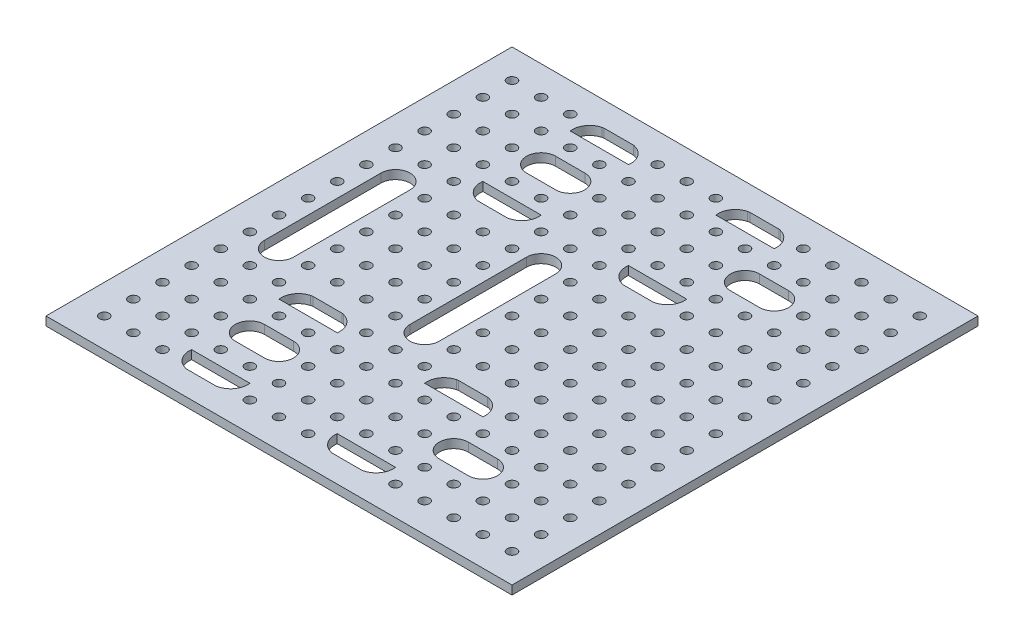
SolidWorks part; units mm, degrees
ref_plane "前视基准面" through (0, 0, 0) normal (0, 0, 1) x (1, 0, 0)
ref_plane "上视基准面" through (0, 0, 0) normal (0, 1, 0) x (1, 0, 0)
ref_plane "右视基准面" through (0, 0, 0) normal (1, 0, 0) x (0, 0, -1)
sketch "草图1" plane through (0, 0, 0) normal (0, 1, 0) x (1, 0, 0)
  line L1 (-80, -80) -> (80, -80)
  line L2 (-80, -80) -> (-80, 80)
  line L3 (-80, 80) -> (80, 80)
  line L4 (80, -80) -> (80, 80)
  line L5 (-80, -80) -> (80, 80) construction
  line L6 (-80, 80) -> (80, -80) construction
  point P0 (0, 0)
  dimension "D1" = 160
  dimension "D2" = 160
extrude "凸台-拉伸1" add sketch "草图1" along normal blind 3 contours L2 L1 L4 L3
sketch "草图3" plane through (0, 3, 0) normal (0, 1, 0) x (1, 0, 0)
  line L0 (-80, 80) -> (80, 80) construction
  line L2 (-80, -80) -> (-80, 80) construction
  circle A0 centre (-70, 70) radius 1.65
  circle A1 centre (-60, 70) radius 1.65
  circle A2 centre (-50, 70) radius 1.65
  circle A3 centre (-40, 70) radius 1.65
  circle A4 centre (-30, 70) radius 1.65
  circle A5 centre (-20, 70) radius 1.65
  circle A6 centre (-10, 70) radius 1.65
  circle A7 centre (0, 70) radius 1.65
  circle A8 centre (10, 70) radius 1.65
  circle A9 centre (20, 70) radius 1.65
  circle A10 centre (30, 70) radius 1.65
  circle A11 centre (40, 70) radius 1.65
  circle A12 centre (50, 70) radius 1.65
  circle A13 centre (60, 70) radius 1.65
  circle A14 centre (70, 70) radius 1.65
  circle A15 centre (-60, 60) radius 1.65
  circle A16 centre (-50, 60) radius 1.65
  circle A17 centre (-40, 60) radius 1.65
  circle A18 centre (-30, 60) radius 1.65
  circle A19 centre (-20, 60) radius 1.65
  circle A20 centre (-10, 60) radius 1.65
  circle A21 centre (0, 60) radius 1.65
  circle A22 centre (10, 60) radius 1.65
  circle A23 centre (20, 60) radius 1.65
  circle A24 centre (30, 60) radius 1.65
  circle A25 centre (40, 60) radius 1.65
  circle A26 centre (50, 60) radius 1.65
  circle A27 centre (60, 60) radius 1.65
  circle A28 centre (70, 60) radius 1.65
  circle A29 centre (-60, 50) radius 1.65
  circle A30 centre (-50, 50) radius 1.65
  circle A31 centre (-40, 50) radius 1.65
  circle A32 centre (-30, 50) radius 1.65
  circle A33 centre (-20, 50) radius 1.65
  circle A34 centre (-10, 50) radius 1.65
  circle A35 centre (0, 50) radius 1.65
  circle A36 centre (10, 50) radius 1.65
  circle A37 centre (20, 50) radius 1.65
  circle A38 centre (30, 50) radius 1.65
  circle A39 centre (40, 50) radius 1.65
  circle A40 centre (50, 50) radius 1.65
  circle A41 centre (60, 50) radius 1.65
  circle A42 centre (70, 50) radius 1.65
  circle A43 centre (-60, 40) radius 1.65
  circle A44 centre (-50, 40) radius 1.65
  circle A45 centre (-40, 40) radius 1.65
  circle A46 centre (-30, 40) radius 1.65
  circle A47 centre (-20, 40) radius 1.65
  circle A48 centre (-10, 40) radius 1.65
  circle A49 centre (0, 40) radius 1.65
  circle A50 centre (10, 40) radius 1.65
  circle A51 centre (20, 40) radius 1.65
  circle A52 centre (30, 40) radius 1.65
  circle A53 centre (40, 40) radius 1.65
  circle A54 centre (50, 40) radius 1.65
  circle A55 centre (60, 40) radius 1.65
  circle A56 centre (70, 40) radius 1.65
  circle A57 centre (-60, 30) radius 1.65
  circle A58 centre (-50, 30) radius 1.65
  circle A59 centre (-40, 30) radius 1.65
  circle A60 centre (-30, 30) radius 1.65
  circle A61 centre (-20, 30) radius 1.65
  circle A62 centre (-10, 30) radius 1.65
  circle A63 centre (0, 30) radius 1.65
  circle A64 centre (10, 30) radius 1.65
  circle A65 centre (20, 30) radius 1.65
  circle A66 centre (30, 30) radius 1.65
  circle A67 centre (40, 30) radius 1.65
  circle A68 centre (50, 30) radius 1.65
  circle A69 centre (60, 30) radius 1.65
  circle A70 centre (70, 30) radius 1.65
  circle A71 centre (-60, 20) radius 1.65
  circle A72 centre (-50, 20) radius 1.65
  circle A73 centre (-40, 20) radius 1.65
  circle A74 centre (-30, 20) radius 1.65
  circle A75 centre (-20, 20) radius 1.65
  circle A76 centre (-10, 20) radius 1.65
  circle A77 centre (0, 20) radius 1.65
  circle A78 centre (10, 20) radius 1.65
  circle A79 centre (20, 20) radius 1.65
  circle A80 centre (30, 20) radius 1.65
  circle A81 centre (40, 20) radius 1.65
  circle A82 centre (50, 20) radius 1.65
  circle A83 centre (60, 20) radius 1.65
  circle A84 centre (70, 20) radius 1.65
  circle A85 centre (-60, 10) radius 1.65
  circle A86 centre (-50, 10) radius 1.65
  circle A87 centre (-40, 10) radius 1.65
  circle A88 centre (-30, 10) radius 1.65
  circle A89 centre (-20, 10) radius 1.65
  circle A90 centre (-10, 10) radius 1.65
  circle A91 centre (0, 10) radius 1.65
  circle A92 centre (10, 10) radius 1.65
  circle A93 centre (20, 10) radius 1.65
  circle A94 centre (30, 10) radius 1.65
  circle A95 centre (40, 10) radius 1.65
  circle A96 centre (50, 10) radius 1.65
  circle A97 centre (60, 10) radius 1.65
  circle A98 centre (70, 10) radius 1.65
  circle A99 centre (-60, 0) radius 1.65
  circle A100 centre (-50, 0) radius 1.65
  circle A101 centre (-40, 0) radius 1.65
  circle A102 centre (-30, 0) radius 1.65
  circle A103 centre (-20, 0) radius 1.65
  circle A104 centre (-10, 0) radius 1.65
  circle A105 centre (0, 0) radius 1.65
  circle A106 centre (10, 0) radius 1.65
  circle A107 centre (20, 0) radius 1.65
  circle A108 centre (30, 0) radius 1.65
  circle A109 centre (40, 0) radius 1.65
  circle A110 centre (50, 0) radius 1.65
  circle A111 centre (60, 0) radius 1.65
  circle A112 centre (70, 0) radius 1.65
  circle A113 centre (-60, -10) radius 1.65
  circle A114 centre (-50, -10) radius 1.65
  circle A115 centre (-40, -10) radius 1.65
  circle A116 centre (-30, -10) radius 1.65
  circle A117 centre (-20, -10) radius 1.65
  circle A118 centre (-10, -10) radius 1.65
  circle A119 centre (0, -10) radius 1.65
  circle A120 centre (10, -10) radius 1.65
  circle A121 centre (20, -10) radius 1.65
  circle A122 centre (30, -10) radius 1.65
  circle A123 centre (40, -10) radius 1.65
  circle A124 centre (50, -10) radius 1.65
  circle A125 centre (60, -10) radius 1.65
  circle A126 centre (70, -10) radius 1.65
  circle A127 centre (-60, -20) radius 1.65
  circle A128 centre (-50, -20) radius 1.65
  circle A129 centre (-40, -20) radius 1.65
  circle A130 centre (-30, -20) radius 1.65
  circle A131 centre (-20, -20) radius 1.65
  circle A132 centre (-10, -20) radius 1.65
  circle A133 centre (0, -20) radius 1.65
  circle A134 centre (10, -20) radius 1.65
  circle A135 centre (20, -20) radius 1.65
  circle A136 centre (30, -20) radius 1.65
  circle A137 centre (40, -20) radius 1.65
  circle A138 centre (50, -20) radius 1.65
  circle A139 centre (60, -20) radius 1.65
  circle A140 centre (70, -20) radius 1.65
  circle A141 centre (-60, -30) radius 1.65
  circle A142 centre (-50, -30) radius 1.65
  circle A143 centre (-40, -30) radius 1.65
  circle A144 centre (-30, -30) radius 1.65
  circle A145 centre (-20, -30) radius 1.65
  circle A146 centre (-10, -30) radius 1.65
  circle A147 centre (0, -30) radius 1.65
  circle A148 centre (10, -30) radius 1.65
  circle A149 centre (20, -30) radius 1.65
  circle A150 centre (30, -30) radius 1.65
  circle A151 centre (40, -30) radius 1.65
  circle A152 centre (50, -30) radius 1.65
  circle A153 centre (60, -30) radius 1.65
  circle A154 centre (70, -30) radius 1.65
  circle A155 centre (-60, -40) radius 1.65
  circle A156 centre (-50, -40) radius 1.65
  circle A157 centre (-40, -40) radius 1.65
  circle A158 centre (-30, -40) radius 1.65
  circle A159 centre (-20, -40) radius 1.65
  circle A160 centre (-10, -40) radius 1.65
  circle A161 centre (0, -40) radius 1.65
  circle A162 centre (10, -40) radius 1.65
  circle A163 centre (20, -40) radius 1.65
  circle A164 centre (30, -40) radius 1.65
  circle A165 centre (40, -40) radius 1.65
  circle A166 centre (50, -40) radius 1.65
  circle A167 centre (60, -40) radius 1.65
  circle A168 centre (70, -40) radius 1.65
  circle A169 centre (-60, -50) radius 1.65
  circle A170 centre (-50, -50) radius 1.65
  circle A171 centre (-40, -50) radius 1.65
  circle A172 centre (-30, -50) radius 1.65
  circle A173 centre (-20, -50) radius 1.65
  circle A174 centre (-10, -50) radius 1.65
  circle A175 centre (0, -50) radius 1.65
  circle A176 centre (10, -50) radius 1.65
  circle A177 centre (20, -50) radius 1.65
  circle A178 centre (30, -50) radius 1.65
  circle A179 centre (40, -50) radius 1.65
  circle A180 centre (50, -50) radius 1.65
  circle A181 centre (60, -50) radius 1.65
  circle A182 centre (70, -50) radius 1.65
  circle A183 centre (-60, -60) radius 1.65
  circle A184 centre (-50, -60) radius 1.65
  circle A185 centre (-40, -60) radius 1.65
  circle A186 centre (-30, -60) radius 1.65
  circle A187 centre (-20, -60) radius 1.65
  circle A188 centre (-10, -60) radius 1.65
  circle A189 centre (0, -60) radius 1.65
  circle A190 centre (10, -60) radius 1.65
  circle A191 centre (20, -60) radius 1.65
  circle A192 centre (30, -60) radius 1.65
  circle A193 centre (40, -60) radius 1.65
  circle A194 centre (50, -60) radius 1.65
  circle A195 centre (60, -60) radius 1.65
  circle A196 centre (70, -60) radius 1.65
  circle A197 centre (-60, -70) radius 1.65
  circle A198 centre (-50, -70) radius 1.65
  circle A199 centre (-40, -70) radius 1.65
  circle A200 centre (-30, -70) radius 1.65
  circle A201 centre (-20, -70) radius 1.65
  circle A202 centre (-10, -70) radius 1.65
  circle A203 centre (0, -70) radius 1.65
  circle A204 centre (10, -70) radius 1.65
  circle A205 centre (20, -70) radius 1.65
  circle A206 centre (30, -70) radius 1.65
  circle A207 centre (40, -70) radius 1.65
  circle A208 centre (50, -70) radius 1.65
  circle A209 centre (60, -70) radius 1.65
  circle A210 centre (70, -70) radius 1.65
  circle A211 centre (-70, 60) radius 1.65
  circle A212 centre (-70, 50) radius 1.65
  circle A213 centre (-70, 40) radius 1.65
  circle A214 centre (-70, 30) radius 1.65
  circle A215 centre (-70, 20) radius 1.65
  circle A216 centre (-70, 10) radius 1.65
  circle A217 centre (-70, 0) radius 1.65
  circle A218 centre (-70, -10) radius 1.65
  circle A219 centre (-70, -20) radius 1.65
  circle A220 centre (-70, -30) radius 1.65
  circle A221 centre (-70, -40) radius 1.65
  circle A222 centre (-70, -50) radius 1.65
  circle A223 centre (-70, -60) radius 1.65
  circle A224 centre (-70, -70) radius 1.65
  dimension "D1" = 3.3
  dimension "D2" = 10
  dimension "D3" = 10
  dimension "D4" = 15
  dimension "D5" = 15
extrude "切除-拉伸1" cut sketch "草图3" against normal blind 3
sketch "草图4" plane through (0, 3, 0) normal (0, 1, 0) x (1, 0, 0)
  line L0 (30, -50) -> (40, -50) construction
  line L3 (30, -45) -> (40, -45)
  line L4 (30, -55) -> (40, -55)
  line L5 (-40, -50) -> (-30, -50) construction
  line L6 (-40, -45) -> (-30, -45)
  line L7 (-40, -55) -> (-30, -55)
  line L8 (-40, 50) -> (-30, 50) construction
  line L9 (-40, 55) -> (-30, 55)
  line L10 (-40, 45) -> (-30, 45)
  line L11 (30, 50) -> (40, 50) construction
  line L12 (30, 55) -> (40, 55)
  line L13 (30, 45) -> (40, 45)
  line L14 (-60, 20) -> (-60, -20) construction
  line L17 (-10, 20) -> (-10, -20) construction
  line L20 (-55, 20) -> (-55, -20)
  line L21 (-65, 20) -> (-65, -20)
  line L22 (-5, 20) -> (-5, -20)
  line L23 (-15, 20) -> (-15, -20)
  line L24 (20, 71.65) -> (10, 71.65)
  line L27 (-30, 71.65) -> (-40, 71.65)
  line L36 (25, 65) -> (5, 65)
  line L37 (25, 35) -> (5, 35)
  line L38 (-25, 35) -> (-45, 35)
  line L39 (-25, 65) -> (-45, 65)
  line L41 (-30, 28.35) -> (-40, 28.35)
  line L42 (20, 28.35) -> (10, 28.35)
  line L43 (0, 0) -> (50000, 0) construction
  line L45 (-25, -65) -> (-45, -65)
  line L46 (-30, -71.65) -> (-40, -71.65)
  line L47 (-25, -35) -> (-45, -35)
  line L48 (-30, -28.35) -> (-40, -28.35)
  line L49 (25, -35) -> (5, -35)
  line L50 (20, -28.35) -> (10, -28.35)
  line L51 (25, -65) -> (5, -65)
  line L52 (20, -71.65) -> (10, -71.65)
  arc A2 (30, -45) -> (30, -55) centre (30, -50) ccw
  arc A3 (40, -55) -> (40, -45) centre (40, -50) ccw
  arc A4 (-40, -45) -> (-40, -55) centre (-40, -50) ccw
  arc A5 (-30, -55) -> (-30, -45) centre (-30, -50) ccw
  arc A6 (-40, 55) -> (-40, 45) centre (-40, 50) ccw
  arc A7 (-30, 45) -> (-30, 55) centre (-30, 50) ccw
  arc A8 (30, 55) -> (30, 45) centre (30, 50) ccw
  arc A9 (40, 45) -> (40, 55) centre (40, 50) ccw
  arc A14 (-55, 20) -> (-65, 20) centre (-60, 20) ccw
  arc A15 (-65, -20) -> (-55, -20) centre (-60, -20) ccw
  arc A16 (-5, 20) -> (-15, 20) centre (-10, 20) ccw
  arc A17 (-15, -20) -> (-5, -20) centre (-10, -20) ccw
  circle A26 centre (20, 70) radius 1.65 construction
  circle A27 centre (20, 30) radius 1.65 construction
  circle A30 centre (-30, 70) radius 1.65 construction
  circle A31 centre (-30, 30) radius 1.65 construction
  arc A32 (25, 65) -> (20, 71.65) centre (19.175, 65.825) ccw
  arc A33 (5, 65) -> (10, 71.65) centre (10.825, 65.825) cw
  circle A34 centre (10, 70) radius 1.65 construction
  arc A35 (25, 35) -> (20, 28.35) centre (19.175, 34.175) cw
  arc A36 (5, 35) -> (10, 28.35) centre (10.825, 34.175) ccw
  circle A37 centre (10, 30) radius 1.65 construction
  arc A38 (-25, 35) -> (-30, 28.35) centre (-30.825, 34.175) cw
  arc A39 (-45, 35) -> (-40, 28.35) centre (-39.175, 34.175) ccw
  circle A40 centre (-40, 30) radius 1.65 construction
  arc A41 (-25, 65) -> (-30, 71.65) centre (-30.825, 65.825) ccw
  arc A42 (-45, 65) -> (-40, 71.65) centre (-39.175, 65.825) cw
  circle A43 centre (-40, 70) radius 1.65 construction
  arc A44 (-25, -65) -> (-30, -71.65) centre (-30.825, -65.825) cw
  arc A45 (-45, -65) -> (-40, -71.65) centre (-39.175, -65.825) ccw
  arc A46 (-25, -35) -> (-30, -28.35) centre (-30.825, -34.175) ccw
  arc A47 (-45, -35) -> (-40, -28.35) centre (-39.175, -34.175) cw
  arc A48 (25, -35) -> (20, -28.35) centre (19.175, -34.175) ccw
  arc A49 (5, -35) -> (10, -28.35) centre (10.825, -34.175) cw
  arc A50 (25, -65) -> (20, -71.65) centre (19.175, -65.825) cw
  arc A51 (5, -65) -> (10, -71.65) centre (10.825, -65.825) ccw
  point P4 (35, -50)
  point P11 (-35, -50)
  point P24 (-35, 50)
  point P33 (35, 50)
  point P42 (-60, 0)
  point P51 (-10, 0)
  point P88 (-30.825, 65.825)
  dimension "D23" = 5.8831
  dimension "D24" = 5.8831
  dimension "D25" = 5.8831
  dimension "D26" = 5.8831
  dimension "D27" = 5.8831
  dimension "D28" = 5.8831
  dimension "D29" = 5.8831
  dimension "D30" = 5.8831
  dimension "D1" = 10
  dimension "D2" = 10
  dimension "D3" = 10
  dimension "D4" = 10
  dimension "D5" = 10
  dimension "D6" = 10
  dimension "D7" = 10
  dimension "D8" = 10
  dimension "D9" = 10
  dimension "D10" = 40
  dimension "D11" = 10
  dimension "D12" = 40
  dimension "D13" = 5
  dimension "D14" = 5
  dimension "D15" = 20
  dimension "D16" = 20
  dimension "D17" = 20
  dimension "D18" = 20
  dimension "D19" = 5
  dimension "D20" = 5
  dimension "D21" = 5
  dimension "D22" = 5
  dimension "D31" = 10
  dimension "D32" = 10
  dimension "D33" = 10
  dimension "D34" = 10
extrude "切除-拉伸2" cut sketch "草图4" against normal blind 10
